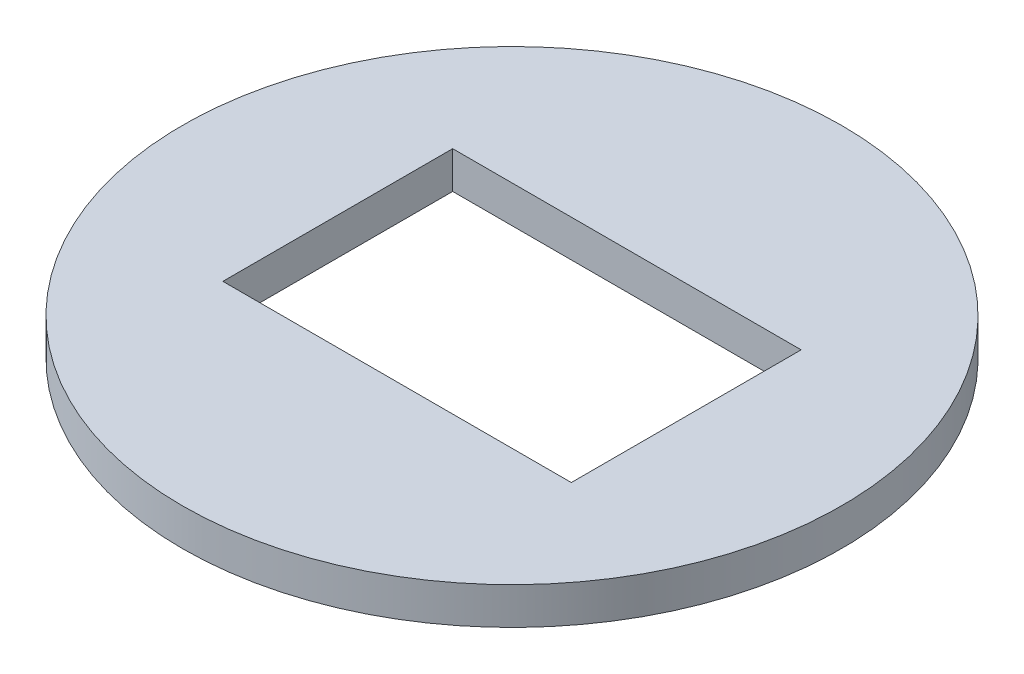
SolidWorks part; units mm, degrees
ref_plane "Front Plane" through (0, 0, 0) normal (0, 0, 1) x (1, 0, 0)
ref_plane "Top Plane" through (0, 0, 0) normal (0, 1, 0) x (1, 0, 0)
ref_plane "Right Plane" through (0, 0, 0) normal (1, 0, 0) x (0, 0, -1)
sketch "Sketch1" plane through (0, 0, 0) normal (0, 1, 0) x (1, 0, 0)
  circle A0 centre (0, 0) radius 88.9
  dimension "D1" = 177.8
extrude "Boss-Extrude1" add sketch "Sketch1" along normal blind 10
extrude "Cut-Extrude1" cut sketch "Sketch2" against normal blind 30
sketch "Sketch2" plane through (0, -10, 0) normal (0, -1, 0) x (1, 0, 0)
  line L1 (-47, 31) -> (47, 31)
  line L2 (-47, 31) -> (-47, -31)
  line L3 (-47, -31) -> (47, -31)
  line L4 (47, 31) -> (47, -31)
  line L5 (-47, 31) -> (47, -31) construction
  line L6 (-47, -31) -> (47, 31) construction
  point P0 (0, 0)
